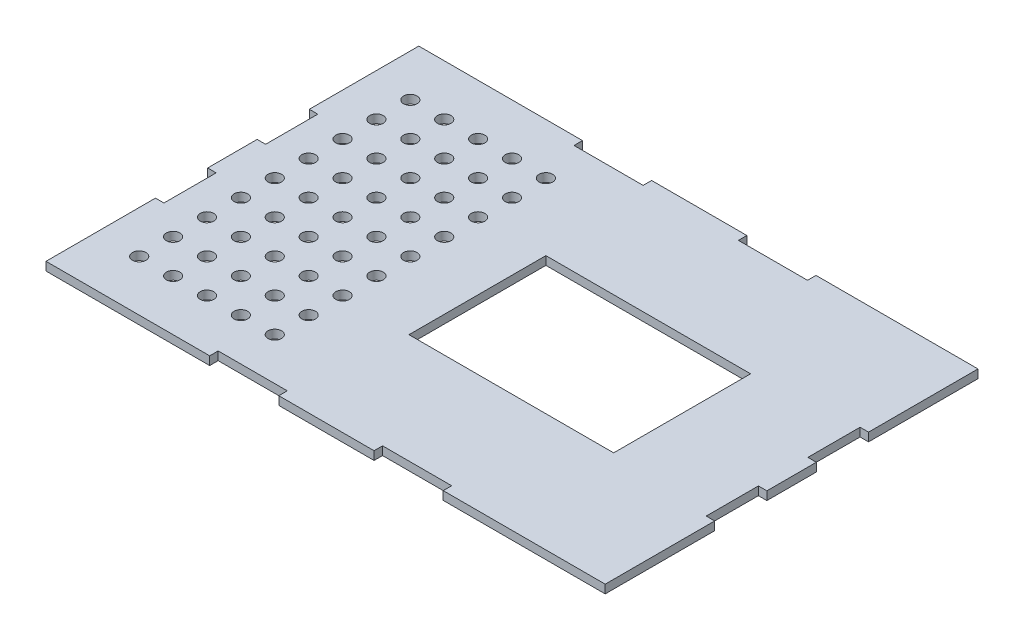
SolidWorks part; units mm, degrees
ref_plane "Front Plane" through (0, 0, 0) normal (0, 0, 1) x (1, 0, 0)
ref_plane "Top Plane" through (0, 0, 0) normal (0, 1, 0) x (1, 0, 0)
ref_plane "Right Plane" through (0, 0, 0) normal (1, 0, 0) x (0, 0, -1)
sketch "Sketch1" plane through (0, 0, 0) normal (0, 1, 0) x (1, 0, 0)
  line L1 (-101.6, -66.675) -> (101.6, -66.675)
  line L2 (-101.6, -66.675) -> (-101.6, 66.675)
  line L3 (-101.6, 66.675) -> (101.6, 66.675)
  line L4 (101.6, -66.675) -> (101.6, 66.675)
  line L5 (-101.6, -66.675) -> (101.6, 66.675) construction
  line L6 (-101.6, 66.675) -> (101.6, -66.675) construction
  point P0 (0, 0)
  dimension "D1" = 203.2
  dimension "D2" = 133.35
extrude "Boss-Extrude1" add sketch "Sketch1" along normal blind 3.175
sketch "Sketch2" plane through (0, 3.175, 0) normal (0, 1, 0) x (1, 0, 0)
  circle A0 centre (-88.9, 50.8) radius 2.54
  circle A1 centre (-76.2, 50.8) radius 2.54
  circle A2 centre (-63.5, 50.8) radius 2.54
  circle A3 centre (-50.8, 50.8) radius 2.54
  circle A4 centre (-76.2, 38.1) radius 2.54
  circle A5 centre (-63.5, 38.1) radius 2.54
  circle A6 centre (-50.8, 38.1) radius 2.54
  circle A7 centre (-76.2, 25.4) radius 2.54
  circle A8 centre (-63.5, 25.4) radius 2.54
  circle A9 centre (-50.8, 25.4) radius 2.54
  circle A10 centre (-76.2, 12.7) radius 2.54
  circle A11 centre (-63.5, 12.7) radius 2.54
  circle A12 centre (-50.8, 12.7) radius 2.54
  circle A13 centre (-76.2, 0) radius 2.54
  circle A14 centre (-63.5, 0) radius 2.54
  circle A15 centre (-50.8, 0) radius 2.54
  circle A16 centre (-76.2, -12.7) radius 2.54
  circle A17 centre (-63.5, -12.7) radius 2.54
  circle A18 centre (-50.8, -12.7) radius 2.54
  circle A19 centre (-76.2, -25.4) radius 2.54
  circle A20 centre (-63.5, -25.4) radius 2.54
  circle A21 centre (-50.8, -25.4) radius 2.54
  circle A22 centre (-76.2, -38.1) radius 2.54
  circle A23 centre (-63.5, -38.1) radius 2.54
  circle A24 centre (-50.8, -38.1) radius 2.54
  circle A25 centre (-76.2, -50.8) radius 2.54
  circle A26 centre (-63.5, -50.8) radius 2.54
  circle A27 centre (-50.8, -50.8) radius 2.54
  circle A28 centre (-88.9, 38.1) radius 2.54
  circle A29 centre (-88.9, 25.4) radius 2.54
  circle A30 centre (-88.9, 12.7) radius 2.54
  circle A31 centre (-88.9, 0) radius 2.54
  circle A32 centre (-88.9, -12.7) radius 2.54
  circle A33 centre (-88.9, -25.4) radius 2.54
  circle A34 centre (-88.9, -38.1) radius 2.54
  circle A35 centre (-88.9, -50.8) radius 2.54
  circle A36 centre (-38.1, 50.8) radius 2.54
  circle A37 centre (-38.1, 38.1) radius 2.54
  circle A38 centre (-38.1, 25.4) radius 2.54
  circle A39 centre (-38.1, 12.7) radius 2.54
  circle A40 centre (-38.1, 0) radius 2.54
  circle A41 centre (-38.1, -12.7) radius 2.54
  circle A42 centre (-38.1, -25.4) radius 2.54
  circle A43 centre (-38.1, -38.1) radius 2.54
  circle A44 centre (-38.1, -50.8) radius 2.54
  dimension "D1" = 5.08
  dimension "D2" = 88.9
  dimension "D3" = 50.8
  dimension "D4" = 5
  dimension "D5" = 9
extrude "Cut-Extrude1" cut sketch "Sketch2" against normal through all
sketch "Sketch3" plane through (0, 3.175, 0) normal (0, 1, 0) x (1, 0, 0)
  line L0 (101.6, 66.675) -> (-101.6, 66.675) construction
  line L1 (-79.121, 66.675) -> (-43.434, 66.675)
  line L2 (-79.121, 66.675) -> (-79.121, 69.85)
  line L3 (-79.121, 69.85) -> (-43.434, 69.85)
  line L4 (-43.434, 66.675) -> (-43.434, 69.85)
  line L5 (-101.6, 66.675) -> (-101.6, -66.675) construction
  line L6 (-17.526, 66.675) -> (18.161, 66.675)
  line L7 (18.161, 66.675) -> (18.161, 69.85)
  line L8 (-17.526, 69.85) -> (18.161, 69.85)
  line L9 (-17.526, 66.675) -> (-17.526, 69.85)
  line L10 (44.069, 66.675) -> (79.756, 66.675)
  line L11 (79.756, 66.675) -> (79.756, 69.85)
  line L12 (44.069, 69.85) -> (79.756, 69.85)
  line L13 (44.069, 66.675) -> (44.069, 69.85)
  line L14 (0, 0) -> (101.6, 0) construction
  line L15 (101.6, -66.675) -> (101.6, 66.675) construction
  line L16 (44.069, -66.675) -> (44.069, -69.85)
  line L17 (44.069, -69.85) -> (79.756, -69.85)
  line L18 (79.756, -66.675) -> (79.756, -69.85)
  line L19 (44.069, -66.675) -> (79.756, -66.675)
  line L20 (-17.526, -66.675) -> (-17.526, -69.85)
  line L21 (-17.526, -69.85) -> (18.161, -69.85)
  line L22 (18.161, -66.675) -> (18.161, -69.85)
  line L23 (-17.526, -66.675) -> (18.161, -66.675)
  line L24 (-43.434, -66.675) -> (-43.434, -69.85)
  line L25 (-79.121, -69.85) -> (-43.434, -69.85)
  line L26 (-79.121, -66.675) -> (-79.121, -69.85)
  line L27 (-79.121, -66.675) -> (-43.434, -66.675)
  point P6 (-61.2775, 66.675)
  dimension "D1" = 3.175
  dimension "D2" = 40.3225
  dimension "D3" = 22.479
  dimension "D4" = 35.687
  dimension "D5" = 3
extrude "Boss-Extrude2" add sketch "Sketch3" against normal blind 3.175
sketch "Sketch4" plane through (0, 3.175, 0) normal (0, 1, 0) x (1, 0, 0)
  line L0 (-101.6, 66.675) -> (-101.6, -66.675) construction
  line L1 (-101.6, 47.371) -> (-104.775, 47.371)
  line L2 (-101.6, 47.371) -> (-101.6, 28.829)
  line L3 (-101.6, 28.829) -> (-104.775, 28.829)
  line L4 (-104.775, 47.371) -> (-104.775, 28.829)
  line L5 (-104.775, 9.271) -> (-104.775, -9.271)
  line L6 (-79.121, 66.675) -> (-101.6, 66.675) construction
  line L7 (-101.6, -9.271) -> (-104.775, -9.271)
  line L8 (-101.6, 9.271) -> (-101.6, -9.271)
  line L9 (-101.6, 9.271) -> (-104.775, 9.271)
  line L10 (-104.775, -28.829) -> (-104.775, -47.371)
  line L11 (-101.6, -47.371) -> (-104.775, -47.371)
  line L12 (-101.6, -28.829) -> (-101.6, -47.371)
  line L13 (-101.6, -28.829) -> (-104.775, -28.829)
  line L14 (0, 0) -> (0, 30.8846) construction
  line L15 (101.6, -28.829) -> (104.775, -28.829)
  line L16 (101.6, -28.829) -> (101.6, -47.371)
  line L17 (101.6, -47.371) -> (104.775, -47.371)
  line L18 (104.775, -28.829) -> (104.775, -47.371)
  line L19 (101.6, 9.271) -> (104.775, 9.271)
  line L20 (101.6, 9.271) -> (101.6, -9.271)
  line L21 (101.6, -9.271) -> (104.775, -9.271)
  line L22 (104.775, 9.271) -> (104.775, -9.271)
  line L23 (104.775, 47.371) -> (104.775, 28.829)
  line L24 (101.6, 28.829) -> (104.775, 28.829)
  line L25 (101.6, 47.371) -> (101.6, 28.829)
  line L26 (101.6, 47.371) -> (104.775, 47.371)
  point P9 (-101.6, 38.1)
  point P10 (-103.1875, 47.371)
  dimension "D1" = 3.175
  dimension "D2" = 28.575
  dimension "D3" = 18.542
  dimension "D4" = 19.304
  dimension "D6" = 38.1
  dimension "D5" = 3
extrude "Boss-Extrude3" add sketch "Sketch4" against normal blind 3.175
sketch "Sketch5" plane through (0, 3.175, 0) normal (0, 1, 0) x (1, 0, 0)
  line L0 (-104.775, -47.371) -> (-104.775, -69.85)
  line L1 (-104.775, -69.85) -> (-79.121, -69.85)
  line L2 (-79.121, -69.85) -> (-79.121, -66.675)
  line L3 (-79.121, -66.675) -> (-101.6, -66.675)
  line L4 (-101.6, -66.675) -> (-101.6, -47.371)
  line L5 (-101.6, -47.371) -> (-104.775, -47.371)
  line L6 (0, 0) -> (0, -32.8131) construction
  line L7 (0, 0) -> (43.4933, 0) construction
  line L8 (-101.6, 47.371) -> (-104.775, 47.371)
  line L9 (-101.6, 66.675) -> (-101.6, 47.371)
  line L10 (-79.121, 66.675) -> (-101.6, 66.675)
  line L11 (-79.121, 69.85) -> (-79.121, 66.675)
  line L12 (-104.775, 69.85) -> (-79.121, 69.85)
  line L13 (-104.775, 47.371) -> (-104.775, 69.85)
  line L14 (104.775, 47.371) -> (104.775, 69.85)
  line L15 (104.775, 69.85) -> (79.121, 69.85)
  line L16 (79.121, 69.85) -> (79.121, 66.675)
  line L17 (79.121, 66.675) -> (101.6, 66.675)
  line L18 (101.6, 66.675) -> (101.6, 47.371)
  line L19 (101.6, 47.371) -> (104.775, 47.371)
  line L20 (101.6, -47.371) -> (104.775, -47.371)
  line L21 (101.6, -66.675) -> (101.6, -47.371)
  line L22 (79.121, -66.675) -> (101.6, -66.675)
  line L23 (79.121, -69.85) -> (79.121, -66.675)
  line L24 (104.775, -69.85) -> (79.121, -69.85)
  line L25 (104.775, -47.371) -> (104.775, -69.85)
extrude "Boss-Extrude4" add sketch "Sketch5" against normal blind 3.175
sketch "Sketch6" plane through (0, 3.175, 0) normal (0, 1, 0) x (1, 0, 0)
  line L0 (101.6, 9.271) -> (101.6, 28.829) construction
  line L1 (63.754, 25.654) -> (-12.954, 25.654)
  line L2 (63.754, 25.654) -> (63.754, -25.654)
  line L3 (63.754, -25.654) -> (-12.954, -25.654)
  line L4 (-12.954, 25.654) -> (-12.954, -25.654)
  line L5 (63.754, 25.654) -> (-12.954, -25.654) construction
  line L6 (63.754, -25.654) -> (-12.954, 25.654) construction
  point P0 (25.4, 0)
  point P5 (0, 0)
  point P6 (0, 0)
  dimension "D1" = 51.308
  dimension "D2" = 76.708
  dimension "D3" = 76.2
extrude "Cut-Extrude2" cut sketch "Sketch6" against normal through all
